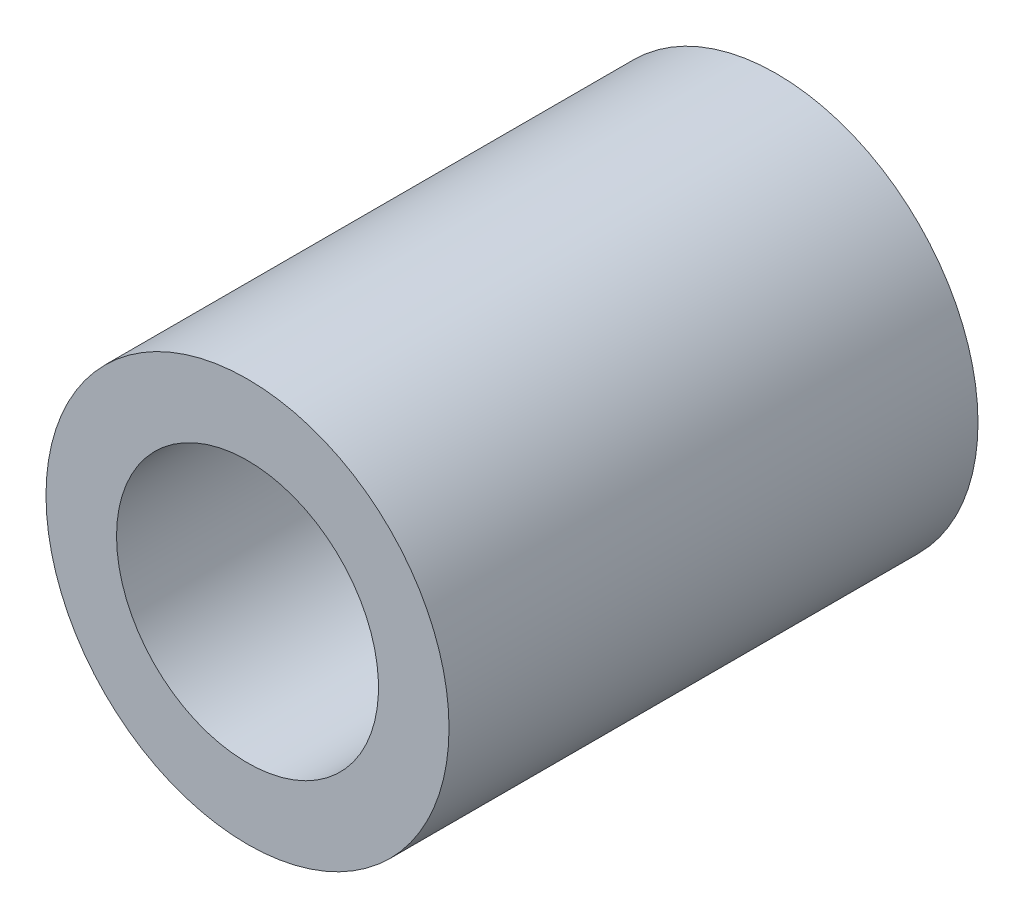
SolidWorks part; units mm, degrees
ref_plane "前视基准面" through (0, 0, 0) normal (0, 0, 1) x (1, 0, 0)
ref_plane "上视基准面" through (0, 0, 0) normal (0, 1, 0) x (1, 0, 0)
ref_plane "右视基准面" through (0, 0, 0) normal (1, 0, 0) x (0, 0, -1)
sketch "草图1" plane through (0, 0, 0) normal (0, 0, 1) x (1, 0, 0)
  circle A0 centre (0, 0) radius 2.6
  circle A1 centre (0, 0) radius 4
  dimension "D1" = 5.2
  dimension "D2" = 8
extrude "凸台-拉伸1" add sketch "草图1" along normal blind 10.5
